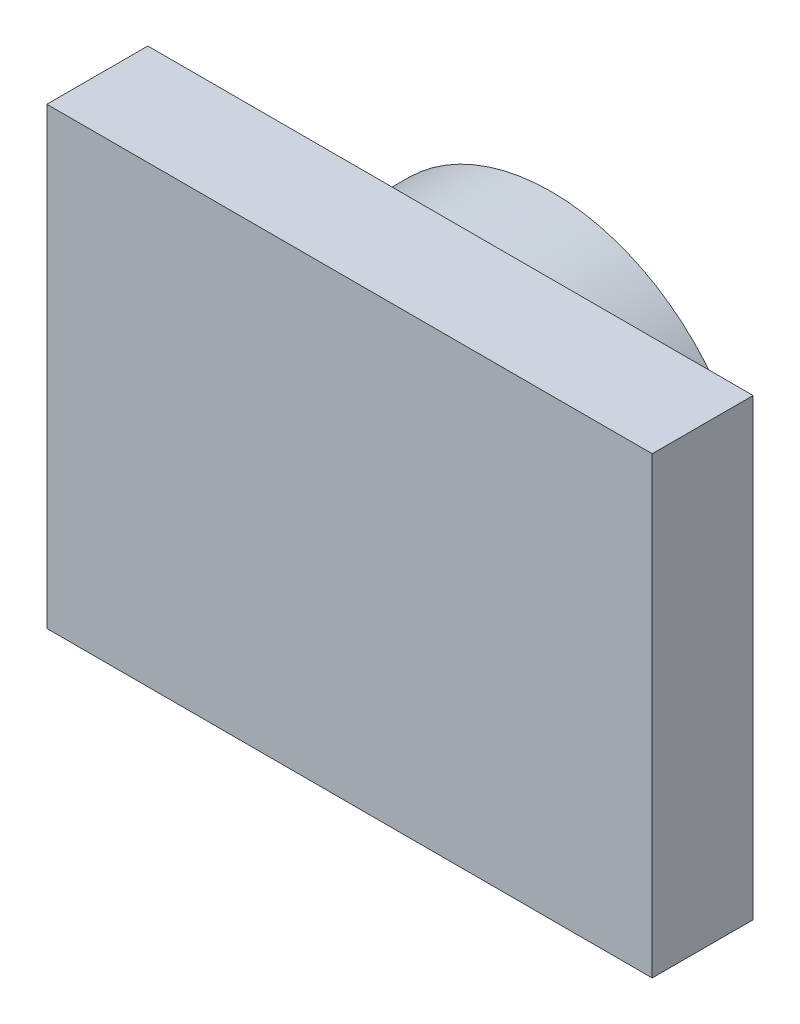
SolidWorks part; units mm, degrees
ref_plane "Alzado" through (0, 0, 0) normal (0, 0, 1) x (1, 0, 0)
ref_plane "Planta" through (0, 0, 0) normal (0, 1, 0) x (1, 0, 0)
ref_plane "Vista lateral" through (0, 0, 0) normal (1, 0, 0) x (0, 0, -1)
sketch "Croquis1" plane through (0, 0, 0) normal (0, 0, 1) x (1, 0, 0)
  circle A0 centre (0, 0) radius 20
  dimension "D1" = 40
extrude "Saliente-Extruir1" add sketch "Croquis1" along normal blind 10
sketch "Croquis2" plane through (0, 0, 10) normal (0, 0, 1) x (1, 0, 0)
  line L1 (-30, 22.5) -> (30, 22.5)
  line L2 (-30, 22.5) -> (-30, -22.5)
  line L3 (-30, -22.5) -> (30, -22.5)
  line L4 (30, 22.5) -> (30, -22.5)
  line L5 (-30, 22.5) -> (30, -22.5) construction
  line L6 (-30, -22.5) -> (30, 22.5) construction
  point P0 (0, 0)
  dimension "D1" = 45
  dimension "D2" = 60
extrude "Saliente-Extruir2" add sketch "Croquis2" along normal blind 10
